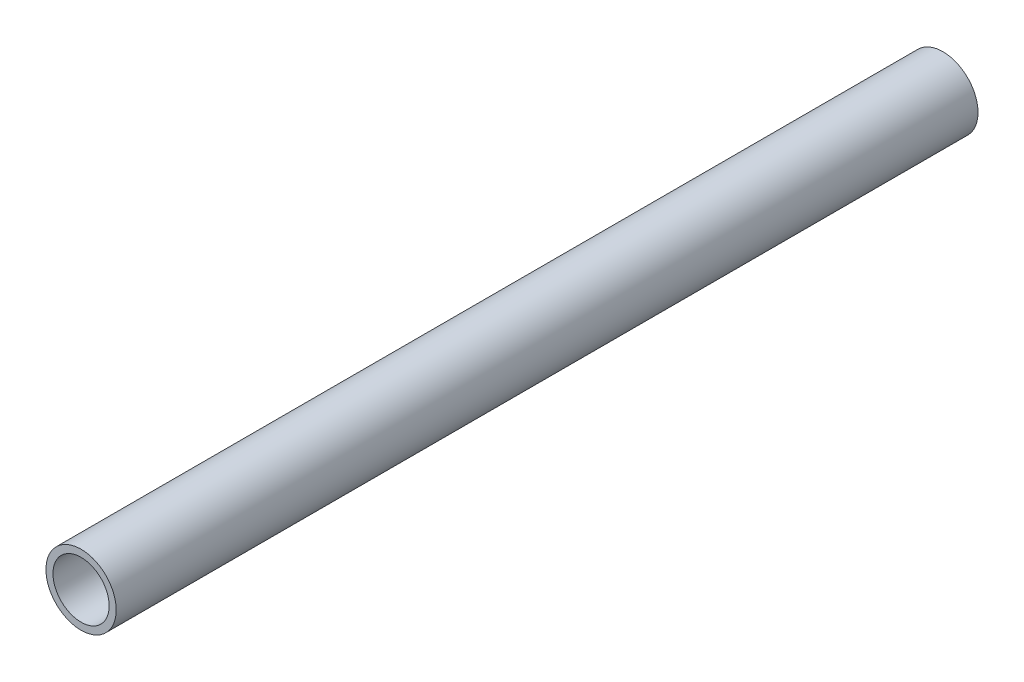
SolidWorks part; units mm, degrees
ref_plane "정면" through (0, 0, 0) normal (0, 0, 1) x (1, 0, 0)
ref_plane "윗면" through (0, 0, 0) normal (0, 1, 0) x (1, 0, 0)
ref_plane "우측면" through (0, 0, 0) normal (1, 0, 0) x (0, 0, -1)
sketch "스케치1" plane through (0, 0, 0) normal (0, 0, 1) x (1, 0, 0)
  circle A0 centre (0, 0) radius 7.5
extrude "보스-돌출1" add sketch "스케치1" along normal mid plane 184
sketch "스케치2" plane through (0, 0, 92) normal (0, 0, 1) x (1, 0, 0)
  circle A0 centre (0, 0) radius 6
extrude "컷-돌출1" cut sketch "스케치2" against normal blind 34.59
sketch "스케치3" plane through (0, 0, -92) normal (0, 0, -1) x (-1, 0, 0)
  circle A0 centre (0, 0) radius 6
extrude "컷-돌출2" cut sketch "스케치3" against normal blind 34.59
